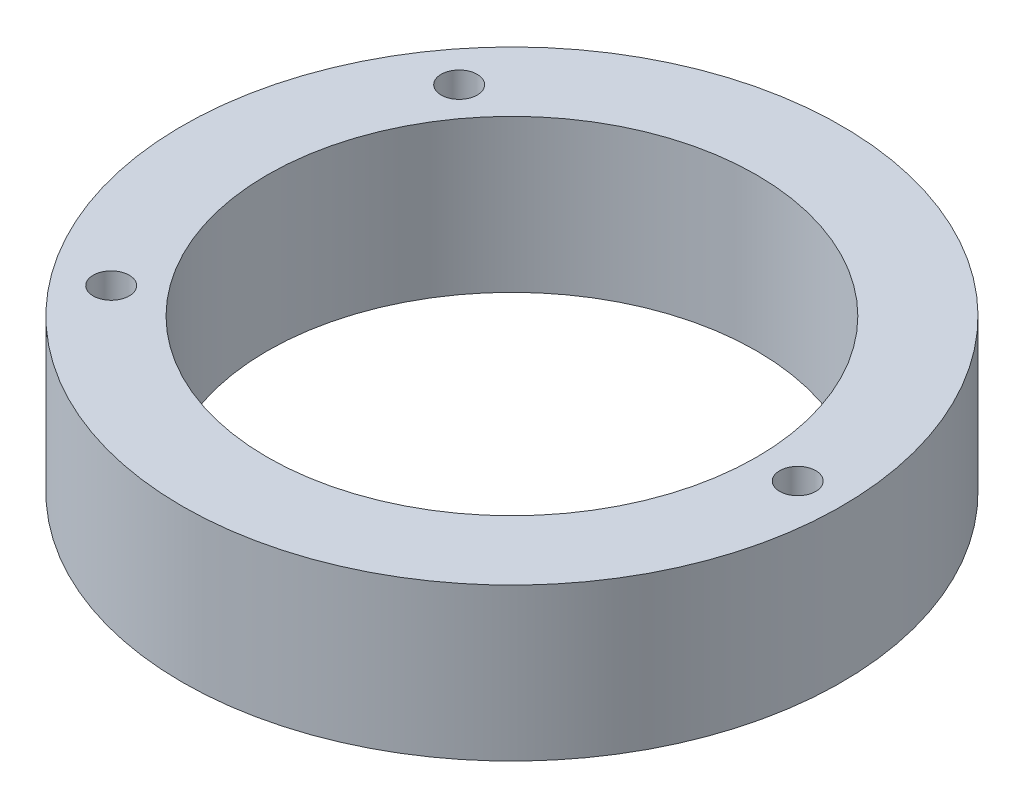
SolidWorks part; units mm, degrees
ref_plane "Front Plane" through (0, 0, 0) normal (0, 0, 1) x (1, 0, 0)
ref_plane "Top Plane" through (0, 0, 0) normal (0, 1, 0) x (1, 0, 0)
ref_plane "Right Plane" through (0, 0, 0) normal (1, 0, 0) x (0, 0, -1)
sketch "Sketch1" plane through (0, 0, 0) normal (0, 1, 0) x (1, 0, 0)
  line L0 (-22.0156, 16.8931) -> (0, 0) construction
  line L1 (0, 0) -> (-22.0156, -16.8931) construction
  line L2 (0, 0) -> (27.75, 0) construction
  line L3 (-22.0156, 16.8931) -> (-22.0156, -16.8931) construction
  circle A0 centre (0, 0) radius 23.75
  circle A1 centre (0, 0) radius 32
  circle A2 centre (27.75, 0) radius 1.75
  circle A3 centre (-22.0156, -16.8931) radius 1.75
  circle A4 centre (-22.0156, 16.8931) radius 1.75
  dimension "D1" = 47.5
  dimension "D2" = 64
  dimension "D5" = 3.5
  dimension "D3" = 75
  dimension "D4" = 27.75
extrude "Boss-Extrude1" add sketch "Sketch1" along normal blind 14.8
